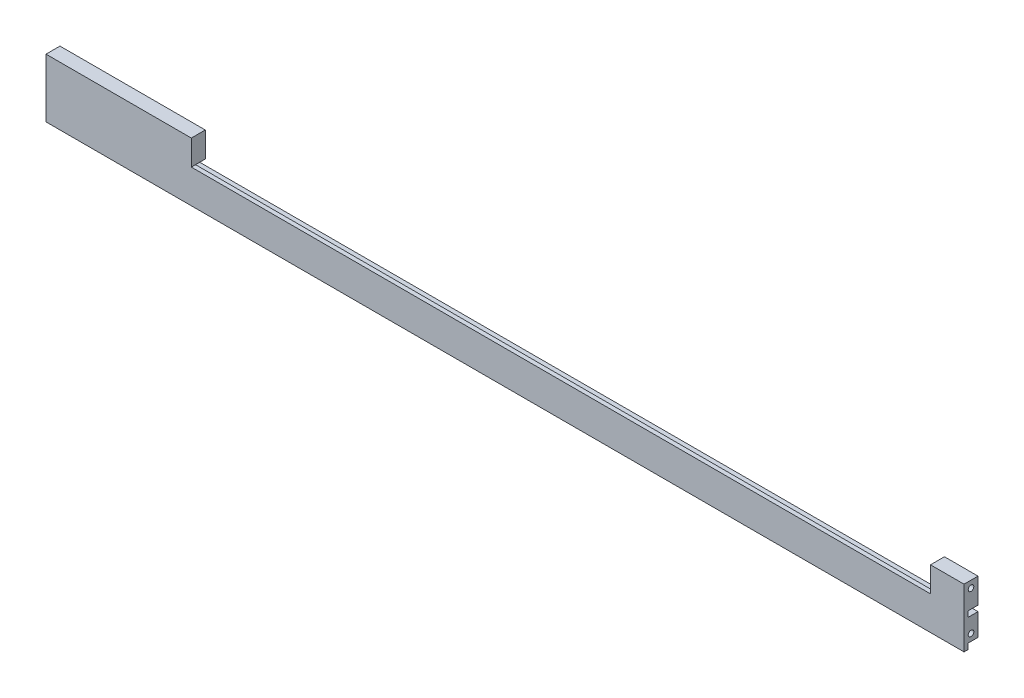
SolidWorks part; units mm, degrees
material "Mahogany"
ref_plane "Front Plane" through (0, 0, 0) normal (0, 0, 1) x (1, 0, 0)
ref_plane "Top Plane" through (0, 0, 0) normal (0, 1, 0) x (1, 0, 0)
ref_plane "Right Plane" through (0, 0, 0) normal (1, 0, 0) x (0, 0, -1)
sketch "Sketch1" plane through (0, 0, 0) normal (0, 0, 1) x (1, 0, 0)
  line L0 (-482.7062, 28.6104) -> (-482.7062, -13.3896)
  line L13 (-482.7062, -13.3896) -> (174.2938, -13.3896)
  line L14 (174.2938, -13.3896) -> (174.2938, 28.6104)
  line L15 (174.2938, 28.6104) -> (150.2938, 28.6104)
  line L16 (150.2938, 28.6104) -> (150.2938, 10.6104)
  line L17 (150.2938, 10.6104) -> (-378.7062, 10.6104)
  line L18 (-378.7062, 10.6104) -> (-378.7062, 28.6104)
  line L19 (-378.7062, 28.6104) -> (-482.7062, 28.6104)
  dimension "D1" = 24
  dimension "D2" = 24
  dimension "D3" = 18
  dimension "D4" = 42
  dimension "D5" = 104
  dimension "D6" = 529
  dimension "D7" = 657
sketch3d "3DSketch1" plane through (0, 0, 0) normal (0, 0, 1) x (1, 0, 0)
extrude "Boss-Extrude1" add sketch "Sketch1" along normal blind 10 contours L17 L18 L19 L0 L13 L14 L15 L16
sketch "Sketch2" plane through (0, 0, 0) normal (0, 0, -1) x (-1, 0, 0)
  line L0 (-174.2938, -13.3896) -> (-174.2938, 28.6104) construction
  line L1 (-174.2938, 10.6104) -> (482.7062, 10.6104)
  line L2 (-174.2938, 10.6104) -> (-174.2938, 6.6104)
  line L3 (-174.2938, 6.6104) -> (482.7062, 6.6104)
  line L4 (482.7062, 10.6104) -> (482.7062, 6.6104)
  line L5 (-150.2938, 10.6104) -> (378.7062, 10.6104) construction
  dimension "D1" = 4
  dimension "D3" = 104
extrude "Cut-Extrude1" cut sketch "Sketch2" against normal blind 7
sketch "Sketch3" plane through (0, 0, 0) normal (0, 0, -1) x (-1, 0, 0)
  line L0 (482.7062, -13.3896) -> (-174.2938, -13.3896) construction
  line L1 (-174.2938, -13.3896) -> (482.7062, -13.3896)
  line L2 (-174.2938, -13.3896) -> (-174.2938, -9.3896)
  line L3 (-174.2938, -9.3896) -> (482.7062, -9.3896)
  line L4 (482.7062, -13.3896) -> (482.7062, -9.3896)
  line L5 (482.7062, 28.6104) -> (482.7062, 10.6104) construction
  dimension "D1" = 4
extrude "Cut-Extrude2" cut sketch "Sketch3" against normal blind 7 contours L2 L1 L4 L3
sketch "Sketch4" plane through (0, -9.3896, 0) normal (0, -1, 0) x (1, 0, 0)
  line L1 (-482.7062, 7) -> (-482.7062, 0) construction
  line L2 (174.2938, 0) -> (-482.7062, 0) construction
  line L3 (174.2938, 7) -> (174.2938, 0) construction
  circle A0 centre (-432.7062, 3.5) radius 1.5
  circle A1 centre (-154.2062, 3.5) radius 1.5
  circle A2 centre (124.2938, 3.5) radius 1.5
  dimension "D1" = 3
  dimension "D6" = 3
  dimension "D5" = 3
  dimension "D2" = 3.5
  dimension "D3" = 50
  dimension "D4" = 328.5
  dimension "D7" = 50
extrude "Cut-Extrude3" cut sketch "Sketch4" against normal blind 12 contours A0 | A1 | A2
sketch "Sketch6" plane through (174.2938, 0, 0) normal (1, 0, 0) x (0, 0, -1)
  line L0 (-10, -13.3896) -> (-10, 28.6104) construction
  line L1 (-10, 28.6104) -> (0, 28.6104) construction
  line L2 (-7, -9.3896) -> (0, -9.3896) construction
  circle A0 centre (-5, 23.6104) radius 2
  circle A1 centre (-5, -4.3896) radius 2
  dimension "D1" = 4
  dimension "D4" = 4
  dimension "D2" = 5
  dimension "D3" = 5
  dimension "D5" = 5
extrude "Cut-Extrude4" cut sketch "Sketch6" against normal blind 10 contours A1 | A0
sketch "Sketch7" plane through (-482.7062, 0, 0) normal (-1, 0, 0) x (0, 0, 1)
  line L0 (10, 28.6104) -> (0, 28.6104) construction
  line L1 (0, 28.6104) -> (0, 10.6104) construction
  line L2 (7, -9.3896) -> (0, -9.3896) construction
  circle A0 centre (5, 23.6104) radius 2
  circle A1 centre (5, -4.3896) radius 2
  dimension "D1" = 4
  dimension "D4" = 4
  dimension "D2" = 5
  dimension "D3" = 5
  dimension "D5" = 5
extrude "Cut-Extrude5" cut sketch "Sketch7" against normal blind 10
